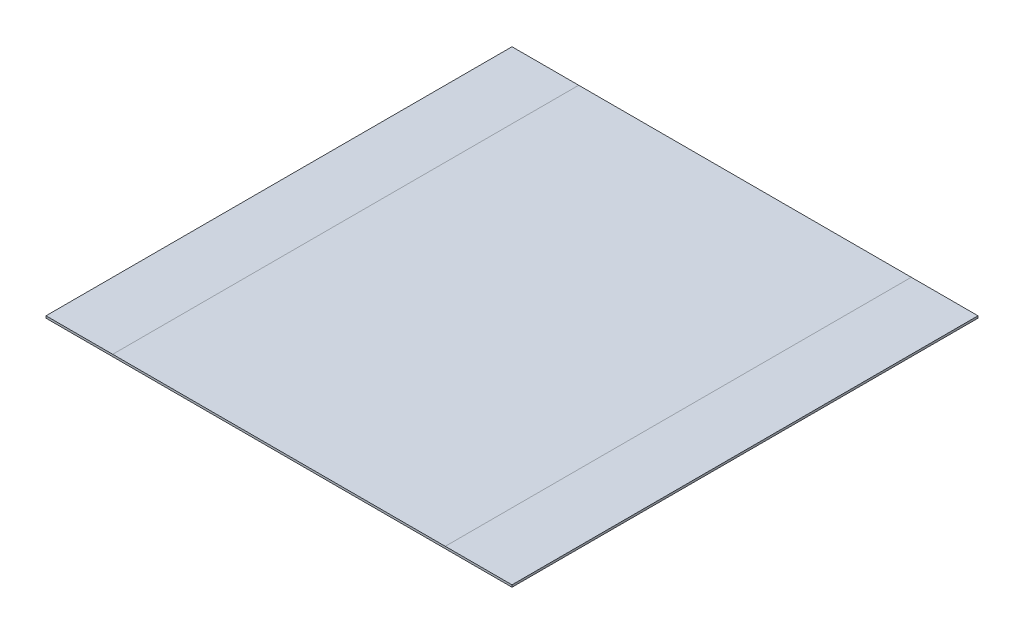
SolidWorks part; units mm, degrees
material "Alumina"
ref_plane "Front Plane" through (0, 0, 0) normal (0, 0, 1) x (1, 0, 0)
ref_plane "Top Plane" through (0, 0, 0) normal (0, 1, 0) x (1, 0, 0)
ref_plane "Right Plane" through (0, 0, 0) normal (1, 0, 0) x (0, 0, -1)
sketch "Sketch1" plane through (0, 0, 0) normal (0, 1, 0) x (1, 0, 0)
  line L1 (-69.85, -69.85) -> (69.85, -69.85)
  line L2 (-69.85, -69.85) -> (-69.85, 69.85)
  line L3 (-69.85, 69.85) -> (69.85, 69.85)
  line L4 (69.85, -69.85) -> (69.85, 69.85)
  line L5 (-69.85, -69.85) -> (69.85, 69.85) construction
  line L6 (-69.85, 69.85) -> (69.85, -69.85) construction
  point P0 (0, 0)
  dimension "D1" = 139.7
extrude "Boss-Extrude1" add sketch "Sketch1" along normal mid plane 0.64
sketch "Sketch2" plane through (0, 0.32, 0) normal (0, 1, 0) x (1, 0, 0)
  line L0 (-69.85, -69.85) -> (69.85, -69.85) construction
  line L1 (-69.85, 69.85) -> (-49.85, 69.85)
  line L2 (-69.85, 69.85) -> (-69.85, -69.85)
  line L3 (-69.85, -69.85) -> (-49.85, -69.85)
  line L4 (-49.85, 69.85) -> (-49.85, -69.85)
  line L6 (69.85, 69.85) -> (49.85, 69.85)
  line L7 (69.85, 69.85) -> (69.85, -69.85)
  line L8 (69.85, -69.85) -> (49.85, -69.85)
  line L9 (49.85, 69.85) -> (49.85, -69.85)
  point P13 (13.4537, -69.85)
  dimension "D1" = 20
split line "Split Line1"
